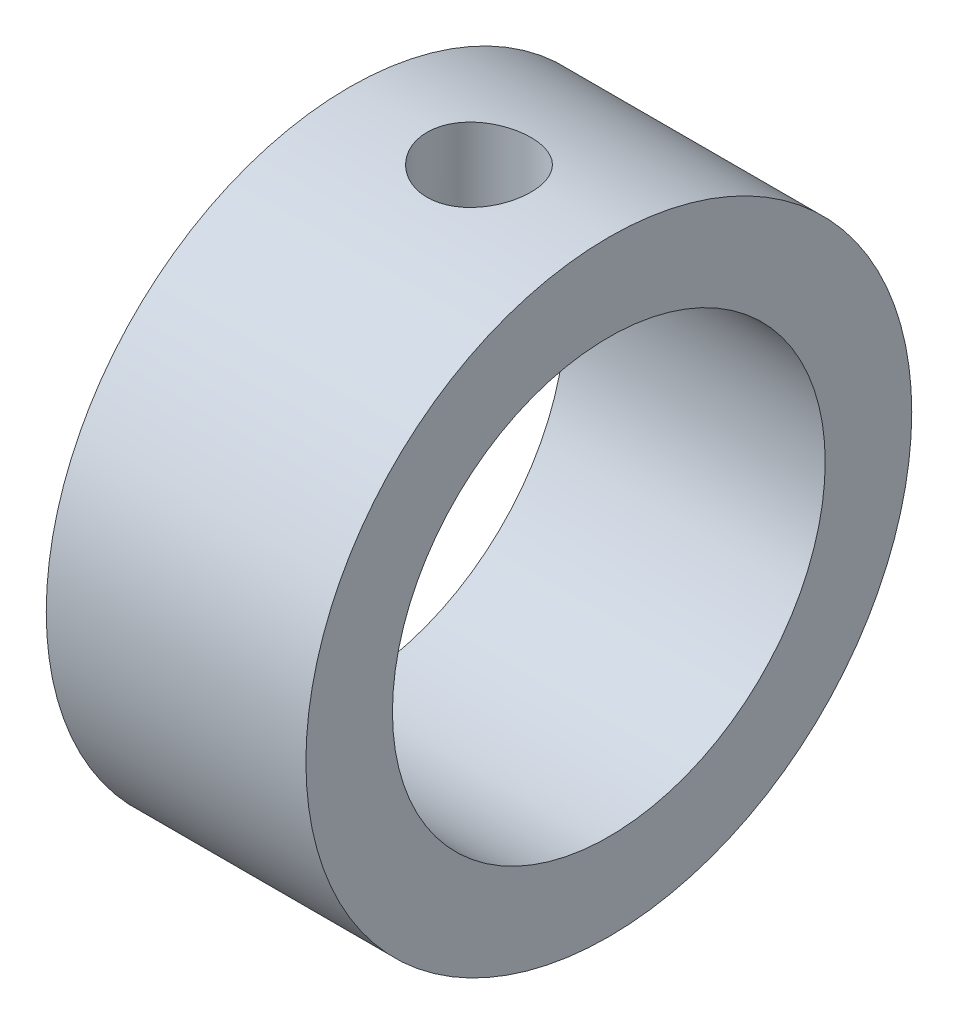
SolidWorks part; units mm, degrees
material "ASTM A36 Steel"
ref_plane "Front Plane" through (0, 0, 0) normal (0, 0, 1) x (1, 0, 0)
ref_plane "Top Plane" through (0, 0, 0) normal (0, 1, 0) x (1, 0, 0)
ref_plane "Right Plane" through (0, 0, 0) normal (1, 0, 0) x (0, 0, -1)
sketch "Sketch1" plane through (0, 0, 0) normal (1, 0, 0) x (0, 0, -1)
  circle A0 centre (0, 0) radius 12.5
  circle A1 centre (0, 0) radius 17.5
  dimension "D1" = 25
  dimension "D2" = 35
extrude "Boss-Extrude1" add sketch "Sketch1" along normal blind 15
sketch "Sketch2" plane through (0, 0, 0) normal (0, 1, 0) x (1, 0, 0)
  line L0 (15, -17.5) -> (15, 17.5) construction
  circle A0 centre (7.5, 0) radius 3
  dimension "D1" = 6
  dimension "D2" = 7.5
extrude "Cut-Extrude1" cut sketch "Sketch2" along normal blind 30
